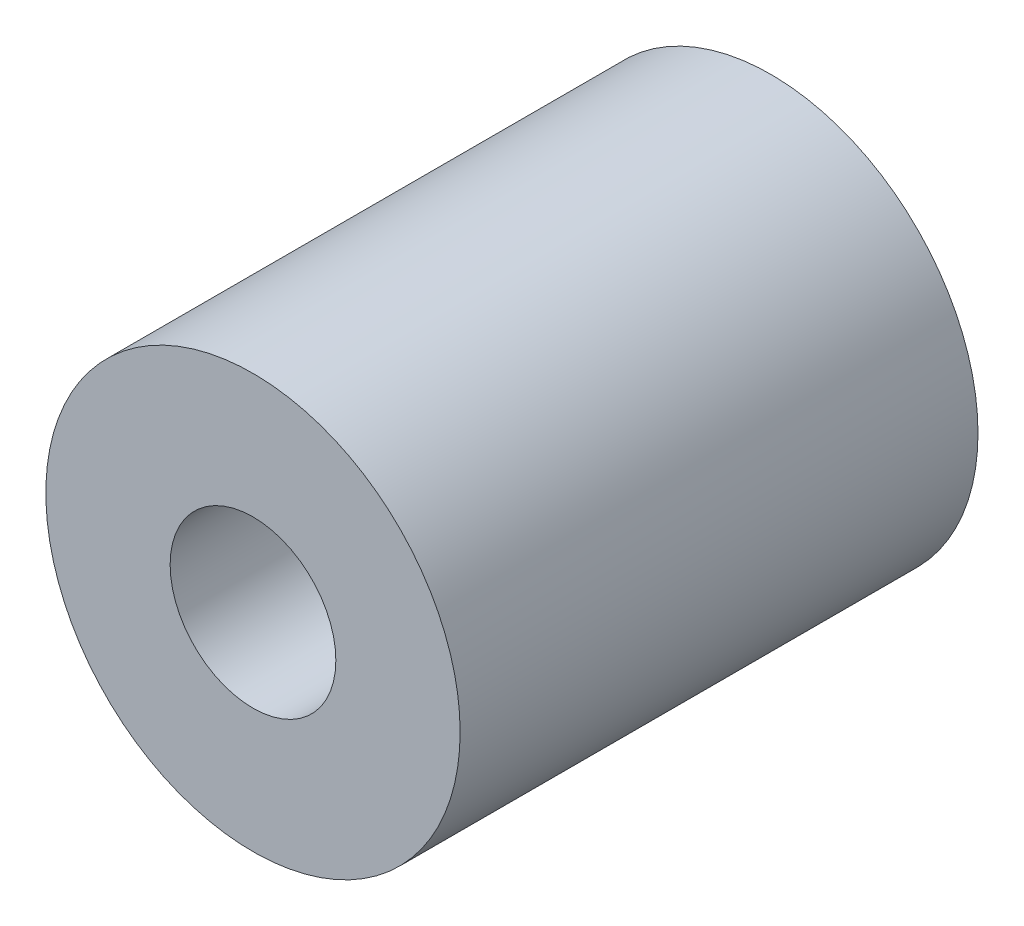
SolidWorks part; units mm, degrees
ref_plane "Front Plane" through (0, 0, 0) normal (0, 0, 1) x (1, 0, 0)
ref_plane "Top Plane" through (0, 0, 0) normal (0, 1, 0) x (1, 0, 0)
ref_plane "Right Plane" through (0, 0, 0) normal (1, 0, 0) x (0, 0, -1)
sketch "Sketch1" plane through (0, 0, 0) normal (0, 0, 1) x (1, 0, 0)
  circle A0 centre (0, 0) radius 4
  circle A1 centre (0, 0) radius 1.6
  dimension "D1" = 8
  dimension "D2" = 3.2
extrude "Boss-Extrude1" add sketch "Sketch1" along normal blind 10
